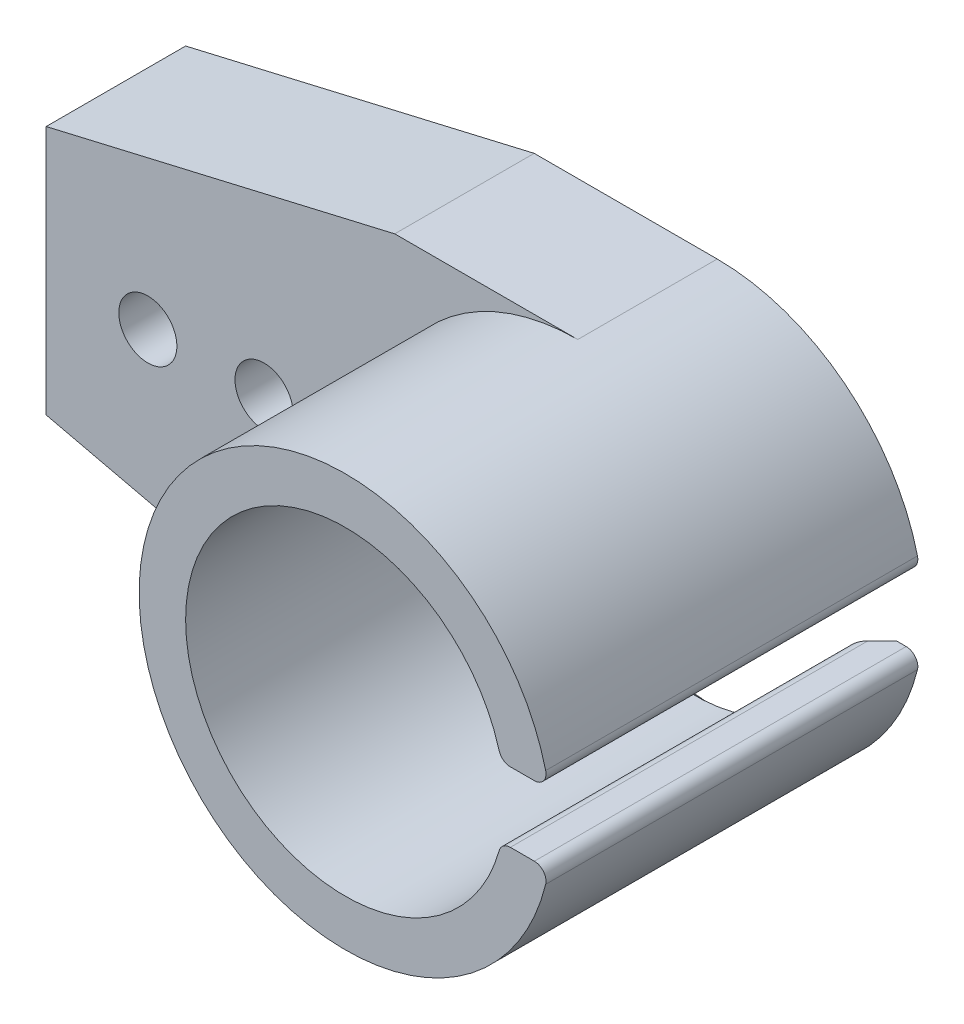
SolidWorks part; units mm, degrees
ref_plane "Plan de face" through (0, 0, 0) normal (0, 0, 1) x (1, 0, 0)
ref_plane "Plan de dessus" through (0, 0, 0) normal (0, 1, 0) x (1, 0, 0)
ref_plane "Plan de droite" through (0, 0, 0) normal (1, 0, 0) x (0, 0, -1)
sketch "Esquisse1" plane through (0, 0, 0) normal (0, 0, 1) x (1, 0, 0)
  line L0 (0, 0) -> (13.75, 0) construction
  line L1 (0, 3) -> (21.7672, 3) construction
  line L2 (0, -3) -> (21.7672, -3) construction
  line L3 (13.4187, 3) -> (17.4946, 3)
  line L4 (17.4946, -3) -> (13.4187, -3)
  line L5 (0, 0) -> (0, 17.75) construction
  line L6 (0, -17.75) -> (-45.75, -17.75)
  line L7 (-45.75, -17.75) -> (-45.75, 17.75)
  line L8 (-45.75, 17.75) -> (0, 17.75)
  circle A0 centre (0, 0) radius 13.75 construction
  arc A1 (13.4187, 3) -> (13.4187, -3) centre (0, 0) ccw
  arc A3 (17.4946, 3) -> (0, 17.75) centre (0, 0) ccw
  arc A4 (17.4946, -3) -> (0, -17.75) centre (0, 0) cw
  circle A5 centre (-37, 0) radius 2.5
  circle A6 centre (-27, 0) radius 2.5
  point P18 (-13.75, 0)
  dimension "D1" = 27.5
  dimension "D2" = 6
  dimension "D3" = 32
  dimension "D4" = 4
  dimension "D6" = 5
  dimension "D5" = 10
  dimension "D7" = 27
extrude "Boss.-Extru.1" add sketch "Esquisse1" along normal blind 32
chamfer "Chanfrein1" distance 2 angle 45 1 edges at (-13.75, 0, 0)
fillet "Congé2" radius 1 4 edges at (17.4946, -3, 16) (17.4946, 3, 16) (13.4187, -3, 17) (13.4187, 3, 17)
sketch "Esquisse2" plane through (0, 0, 0) normal (0, 0, -1) x (-1, 0, 0)
  line L0 (45.75, 10.1) -> (27, 10.1)
  line L1 (45.75, 17.75) -> (45.75, -17.75) construction
  line L2 (27, -10.1) -> (45.75, -10.1)
  line L3 (45.75, -10.1) -> (45.75, 10.1)
  arc A0 (27, 10.1) -> (27, -10.1) centre (27, 0) ccw
  circle A1 centre (27, 0) radius 2.5 construction
  dimension "D1" = 20.2
extrude "Enlèv. mat.-Extru.1" cut sketch "Esquisse2" against normal blind 2
sketch "Esquisse3" plane through (0, 0, 32) normal (0, 0, 1) x (1, 0, 0)
  line L0 (0, 17.75) -> (-45.75, 17.75) construction
  line L1 (0, 17.75) -> (-45.75, 17.75)
  line L2 (-45.75, 17.75) -> (-45.75, -17.75)
  line L3 (-45.75, -17.75) -> (0, -17.75)
  line L4 (-45.75, 17.75) -> (-45.75, -17.75) construction
  arc A1 (0, 17.75) -> (0, -17.75) centre (0, 0) ccw
  arc A2 (17.2364, 4.2388) -> (0, 17.75) centre (0, 0) ccw construction
  arc A3 (0, -17.75) -> (17.2364, -4.2388) centre (0, 0) ccw construction
extrude "Enlèv. mat.-Extru.2" cut sketch "Esquisse3" against normal blind 20
sketch "Esquisse5" plane through (0, 0, 12) normal (0, 0, 1) x (1, 0, 0)
  line L0 (-15.75, 17.75) -> (-45.75, 10.75)
  line L1 (0, 17.75) -> (-45.75, 17.75) construction
  line L2 (-45.75, 17.75) -> (-45.75, -17.75) construction
  line L3 (-45.75, 10.75) -> (-45.75, 17.75)
  line L4 (-45.75, 17.75) -> (-15.75, 17.75)
  line L5 (-45.75, 0) -> (0, 0) construction
  line L6 (-45.75, -17.75) -> (-15.75, -17.75)
  line L7 (-45.75, -10.75) -> (-45.75, -17.75)
  line L8 (-15.75, -17.75) -> (-45.75, -10.75)
  dimension "D1" = 7
  dimension "D2" = 30
extrude "Enlèv. mat.-Extru.3" cut sketch "Esquisse5" against normal through all
